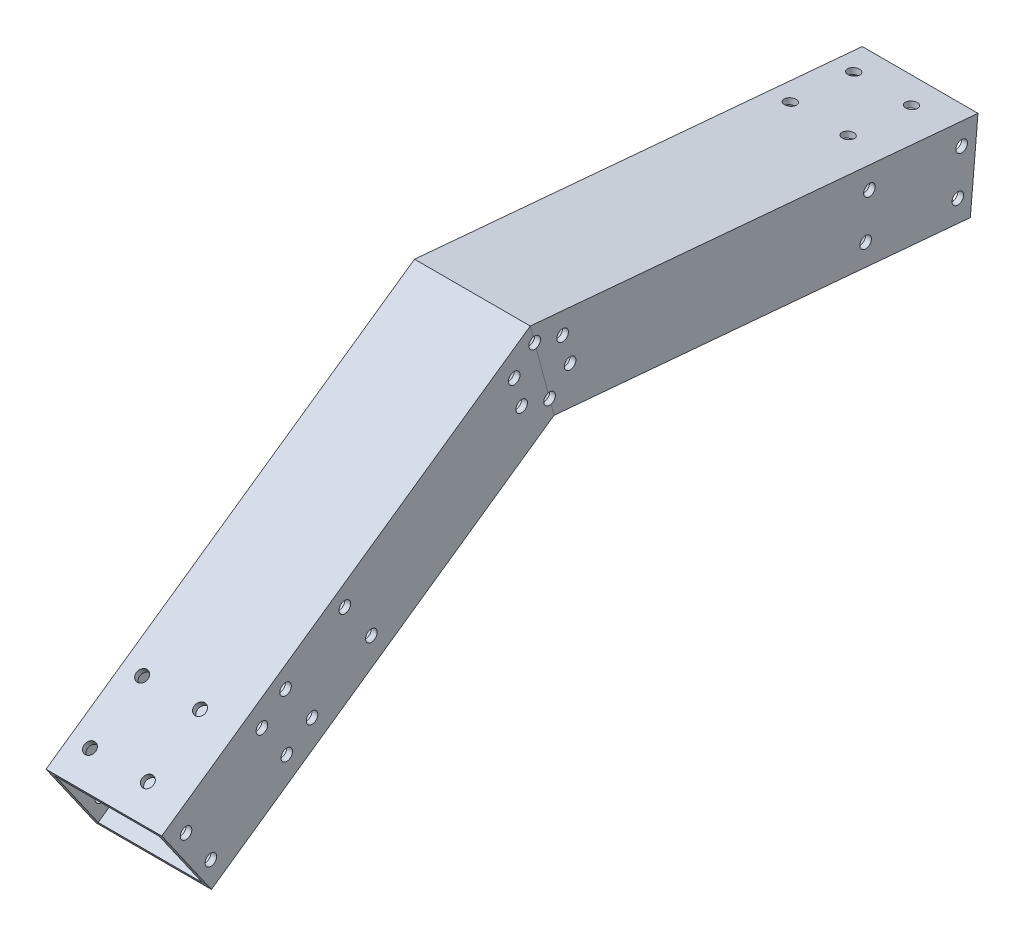
SolidWorks part; units mm, degrees
ref_plane "前视基准面" through (0, 0, 0) normal (0, 0, 1) x (1, 0, 0)
ref_plane "上视基准面" through (0, 0, 0) normal (0, 1, 0) x (1, 0, 0)
ref_plane "右视基准面" through (0, 0, 0) normal (1, 0, 0) x (0, 0, -1)
other "质心 (COM)"
sketch "草图1" plane through (0, 0, 0) normal (1, 0, 0) x (0, 0, -1)
  line L0 (-122.971, -42.5565) -> (0, 43.3396)
  line L1 (0, 43.3396) -> (149.4142, 30.0957)
  dimension "D1" = 150
  dimension "D2" = 150
  dimension "D3" = 140
other "方形管 20 X 20 X 2(1)"
ref_plane "基准面1" through (0, -42.5565, 122.971) normal (0, 0.5726, -0.8198) x (0, 0.8198, 0.5726)
sketch "Sketch1" plane through (0, -42.5565, 122.971) normal (0, 0.5726, -0.8198) x (0, 0.8198, 0.5726)
  line L0 (0, 0) -> (-96.4181, 0) construction
  line L1 (-15.2738, -20) -> (14.7262, -20)
  line L2 (-15.2738, -20) -> (-15.2738, 20)
  line L3 (-15.2738, 20) -> (14.7262, 20)
  line L4 (14.7262, -20) -> (14.7262, 20)
  line L7 (-13.2738, -18) -> (12.7262, -18)
  line L8 (-13.2738, -18) -> (-13.2738, 18)
  line L9 (-13.2738, 18) -> (12.7262, 18)
  line L10 (12.7262, -18) -> (12.7262, 18)
  point P0 (-0.2738, 0)
  point P5 (-0.2738, 6.4436)
  dimension "D1" = 30
  dimension "D2" = 40
  dimension "D3" = 26
  dimension "D4" = 36
  dimension "D5" = 2
  dimension "D6" = 0
  dimension "D7" = 18
sketch "草图3" plane through (0, 41.2004, 28.7788) normal (0, 0.8198, 0.5726) x (1, 0, 0)
  line L0 (-20, -125.182) -> (20, -125.182) construction
  line L1 (-20, 30.1779) -> (-20, -125.182) construction
  circle A0 centre (-13, -93.182) radius 2
  circle A1 centre (7, -93.182) radius 2
  circle A2 centre (7, -115.182) radius 2
  circle A3 centre (-13, -115.182) radius 2
  dimension "D1" = 10
  dimension "D2" = 10
  dimension "D3" = 32
  dimension "D4" = 32
  dimension "D5" = 7
  dimension "D6" = 7
  dimension "D7" = 27
  dimension "D8" = 27
  dimension "D9" = 4
  dimension "D10" = 4
  dimension "D11" = 4
  dimension "D12" = 4
extrude "切除-拉伸1" cut sketch "草图3" against normal blind 50
sketch "草图4" plane through (0, 57.6705, -5.1119) normal (0, 0.9961, -0.0883) x (1, 0, 0)
  line L0 (-20, 146.1734) -> (20, 146.1734) construction
  line L1 (-20, 146.1734) -> (-20, -9.1865) construction
  circle A0 centre (-13, 136.1734) radius 2
  circle A1 centre (7, 136.1734) radius 2
  circle A2 centre (7, 114.1734) radius 2
  circle A3 centre (-13, 114.1734) radius 2
  dimension "D1" = 10
  dimension "D2" = 10
  dimension "D4" = 32
  dimension "D5" = 7
  dimension "D6" = 7
  dimension "D7" = 27
  dimension "D8" = 27
  dimension "D9" = 4
  dimension "D10" = 4
  dimension "D11" = 4
  dimension "D12" = 4
  dimension "D3" = 32
extrude "切除-拉伸2" cut sketch "草图4" against normal blind 50
sketch "草图5" plane through (20, 0, 0) normal (1, 0, 0) x (0, 0, -1)
  line L0 (-131.4038, -30.4839) -> (-114.2246, -55.0781) construction
  line L1 (-4.0387, 58.4816) -> (-131.4038, -30.4839) construction
  line L2 (4.1889, 27.6346) -> (-114.2246, -55.0781) construction
  circle A0 centre (-88.6172, -7.9159) radius 2
  circle A1 centre (-68.1221, 6.4001) radius 2
  circle A2 centre (-58.9598, -6.7168) radius 2
  circle A3 centre (-79.455, -21.0328) radius 2
  dimension "D1" = 48
  dimension "D2" = 48
  dimension "D3" = 73
  dimension "D4" = 73
  dimension "D5" = 6
  dimension "D6" = 4
  dimension "D7" = 6
  dimension "D8" = 8
  dimension "D9" = 8
  dimension "D10" = 4
  dimension "D11" = 4
  dimension "D12" = 4
extrude "切除-拉伸3" cut sketch "草图5" against normal through all
sketch "草图6" plane through (20, 0, 0) normal (1, 0, 0) x (0, 0, -1)
  line L0 (-131.4038, -30.4839) -> (-114.2246, -55.0781) construction
  line L1 (-4.0387, 58.4816) -> (-131.4038, -30.4839) construction
  line L2 (4.1889, 27.6346) -> (-114.2246, -55.0781) construction
  circle A0 centre (-123.0099, -33.7692) radius 2
  circle A1 centre (-96.7761, -15.4447) radius 2
  circle A2 centre (-88.1865, -27.7418) radius 2
  circle A3 centre (-114.4203, -46.0663) radius 2
  dimension "D1" = 5
  dimension "D2" = 37
  dimension "D3" = 5
  dimension "D4" = 37
  dimension "D5" = 7.5
  dimension "D6" = 7.5
  dimension "D7" = 7.5
  dimension "D8" = 4
  dimension "D9" = 7.5
  dimension "D10" = 4
  dimension "D11" = 4
  dimension "D12" = 4
extrude "切除-拉伸4" cut sketch "草图6" against normal through all
sketch "草图7" plane through (20, 0, 0) normal (1, 0, 0) x (0, 0, -1)
  line L0 (150.7144, 44.7644) -> (-4.0387, 58.4816) construction
  line L1 (148.0656, 14.8815) -> (4.1889, 27.6346) construction
  line L2 (143.7473, 22.7937) -> (145.0717, 37.7351) construction
  line L3 (145.0717, 37.7351) -> (113.1967, 40.5605) construction
  line L4 (150.7144, 44.7644) -> (148.0656, 14.8815) construction
  line L7 (113.1967, 40.5605) -> (111.8723, 25.6191) construction
  line L8 (111.8723, 25.6191) -> (143.7473, 22.7937) construction
  circle A0 centre (145.0717, 37.7351) radius 2
  circle A1 centre (143.7473, 22.7937) radius 2
  circle A2 centre (111.8723, 25.6191) radius 2
  circle A3 centre (113.1967, 40.5605) radius 2
  dimension "D1" = 5
  dimension "D2" = 7.5
  dimension "D3" = 7.5
  dimension "D4" = 37
extrude "切除-拉伸5" cut sketch "草图7" against normal through all
sketch "草图8" plane through (20, 0, 0) normal (1, 0, 0) x (0, 0, -1)
  line L0 (4.1889, 27.6346) -> (-4.0387, 58.4816) construction
  circle A0 centre (0.0694, 53.0581) radius 2 construction
  circle A1 centre (8.7297, 48.1005) radius 2 construction
  circle A2 centre (8.7297, 38.1005) radius 2 construction
  circle A3 centre (0.0694, 33.1005) radius 2 construction
  circle A4 centre (-8.5908, 38.1005) radius 2 construction
  circle A5 centre (-8.5908, 48.1005) radius 2 construction
  circle A6 centre (0.0751, 43.0581) radius 10 construction
  circle A7 centre (-2.5021, 52.7203) radius 2
  circle A8 centre (7.1542, 50.1211) radius 2
  circle A9 centre (9.7314, 40.4589) radius 2
  circle A10 centre (2.6522, 33.3959) radius 2
  circle A11 centre (-7.004, 35.9951) radius 2
  circle A12 centre (-9.5812, 45.6573) radius 2
  point P0 (0.0751, 43.0581)
  point P16 (0.0694, 43.1005)
  point P32 (0.0751, 43.0581)
  dimension "D1" = 4
  dimension "D2" = 6
extrude "切除-拉伸6" cut sketch "草图8" against normal through all
